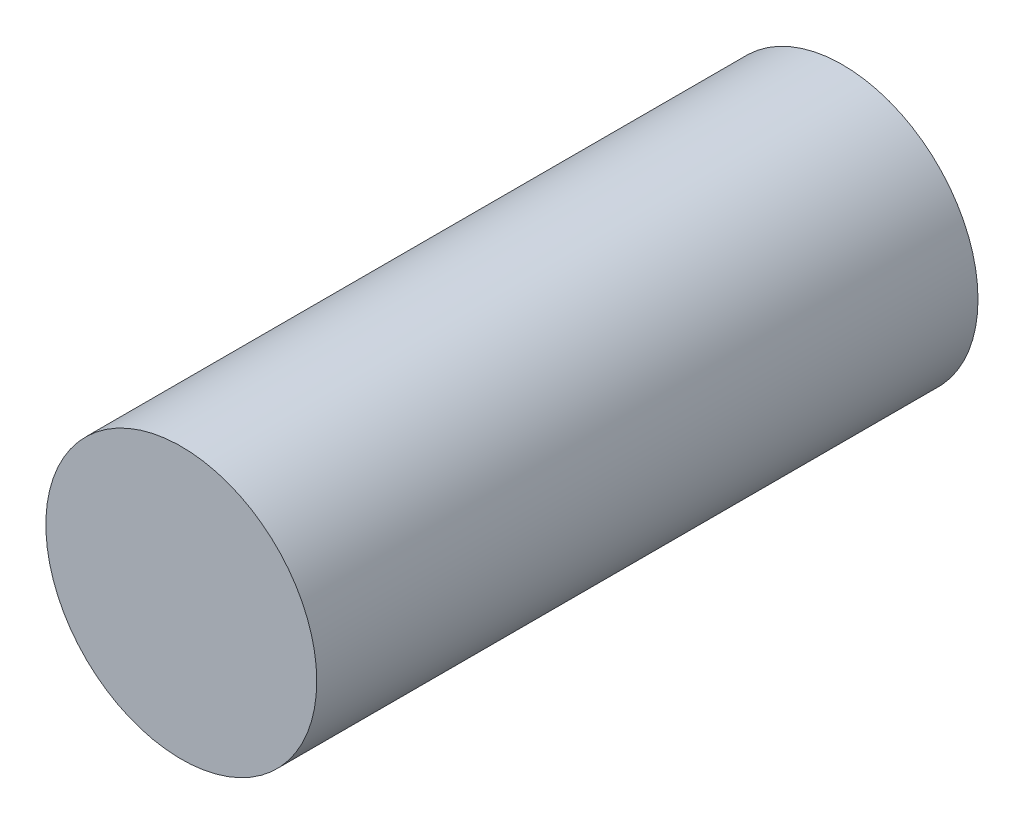
SolidWorks part; units mm, degrees
ref_plane "Front Plane" through (0, 0, 0) normal (0, 0, 1) x (1, 0, 0)
ref_plane "Top Plane" through (0, 0, 0) normal (0, 1, 0) x (1, 0, 0)
ref_plane "Right Plane" through (0, 0, 0) normal (1, 0, 0) x (0, 0, -1)
sketch "Planform" plane through (0, 0, 0) normal (0, 1, 0) x (1, 0, 0)
  line L0 (0, 0) -> (0, -7497.1177)
  line L1 (-17711.9405, -11444.2752) -> (-17711.9405, -14068.2664)
  line L2 (0, -1874.2794) -> (-17711.9405, -12100.273) construction
  line L3 (0, -1874.2794) -> (-6644.0672, -1874.2794) construction
  line L4 (0, 0) -> (-17711.9405, -11444.2752)
  line L5 (0, -7497.1177) -> (-17711.9405, -14068.2664)
  dimension "D1" = 7497.1177
  dimension "D2" = 2623.9912
  dimension "D3" = 1874.2794
  dimension "D4" = 655.9978
  dimension "D5" = 30
  dimension "D6" = 17711.9405
sketch "Sketch1" plane through (0, 0, 0) normal (0, 0, 1) x (1, 0, 0)
  circle A0 centre (0, 0) radius 1209.8064
  dimension "D1" = 2419.6129
extrude "Nacelle body" add sketch "Sketch1" along normal blind 5906.115
sketch "Black front" plane through (0, 0, 5906.115) normal (0, 0, 1) x (1, 0, 0)
  line L0 (59.2242, 1082.815) -> (229.8908, 1082.815) construction
sketch "Location" plane through (0, 0, 0) normal (0, 1, 0) x (1, 0, 0)
  line L0 (-1209.8064, -1066.8892) -> (1209.8064, -1066.8892)
  line L1 (1209.8064, 0) -> (-1209.8064, 0)
  line L2 (1209.8064, 0) -> (1209.8064, -5906.115)
  line L3 (1209.8064, -5906.115) -> (-1209.8064, -5906.115)
  line L4 (-1209.8064, 0) -> (-1209.8064, -5906.115)
  line L5 (-1209.8064, 0) -> (1209.8064, -5906.115)
  line L6 (1209.8064, 0) -> (-1209.8064, -5906.115)
  line L7 (1209.8064, -2953.0575) -> (-1209.8064, -2953.0575)
  line L8 (0, -2953.0575) -> (0, 0)
  line L9 (-1209.8064, -1066.8892) -> (1209.8064, -1066.8892)
  point P11 (0, -2953.0575)
  point P14 (0, -1066.8892)
  dimension "D1" = 2419.6129
  dimension "D2" = 4839.2257
equation "\"Diameter\"= 7.938362438"
equation "\"Length\"= 19.37701766"
equation "\"D1@Sketch1\"=\"Diameter\""
equation "\"D1@Nacelle body\"=\"Length\""
equation "\"D2@Location\"=\"Diameter\"*2"
